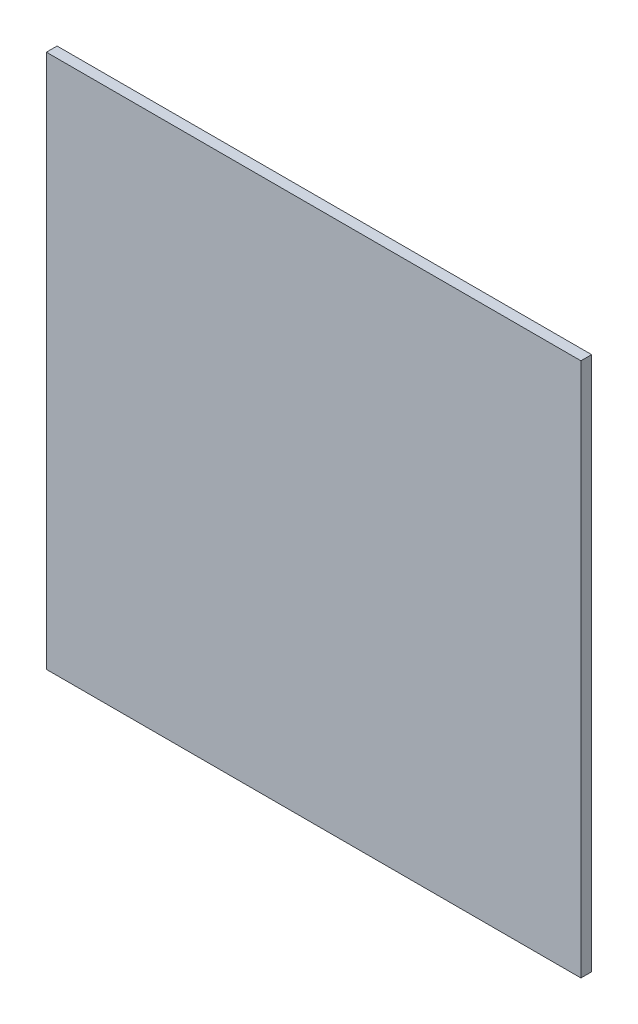
SolidWorks part; units mm, degrees
ref_plane "Plano frontal" through (0, 0, 0) normal (0, 0, 1) x (1, 0, 0)
ref_plane "Plano superior" through (0, 0, 0) normal (0, 1, 0) x (1, 0, 0)
ref_plane "Plano direito" through (0, 0, 0) normal (1, 0, 0) x (0, 0, -1)
sketch "Esboço1" plane through (0, 0, 0) normal (0, 0, 1) x (1, 0, 0)
  line L1 (-75, 75) -> (75, 75)
  line L2 (-75, 75) -> (-75, -75)
  line L3 (-75, -75) -> (75, -75)
  line L4 (75, 75) -> (75, -75)
  line L5 (-75, 75) -> (75, -75) construction
  line L6 (-75, -75) -> (75, 75) construction
  point P0 (0, 0)
  dimension "D1" = 150
extrude "Ressalto-extrusão1" add sketch "Esboço1" along normal blind 3
ref_plane "Plano1" through (0, 0, 0) normal (0, 1, 0) x (1, 0, 0)
ref_plane "Plano2" through (0, 0, 0) normal (1, 0, 0) x (0, 0, -1)
